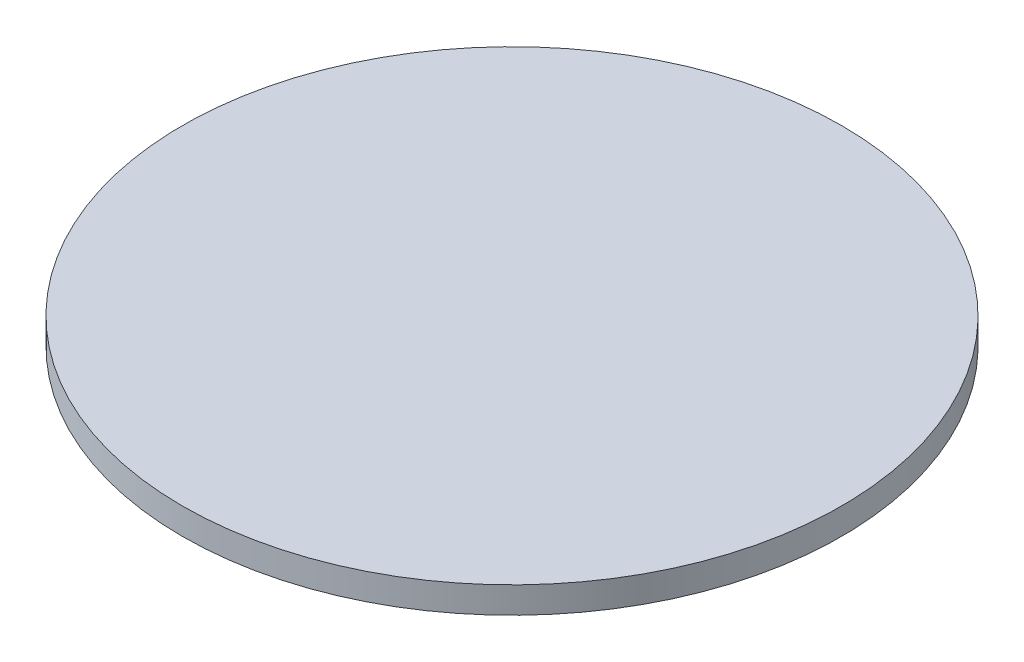
SolidWorks part; units mm, degrees
ref_plane "Front Plane" through (0, 0, 0) normal (0, 0, 1) x (1, 0, 0)
ref_plane "Top Plane" through (0, 0, 0) normal (0, 1, 0) x (1, 0, 0)
ref_plane "Right Plane" through (0, 0, 0) normal (1, 0, 0) x (0, 0, -1)
sketch "Sketch1" plane through (0, 0, 0) normal (0, 1, 0) x (1, 0, 0)
  circle A0 centre (0, 0) radius 10
extrude "Boss-Extrude1" add sketch "Sketch1" along normal blind 0.8
